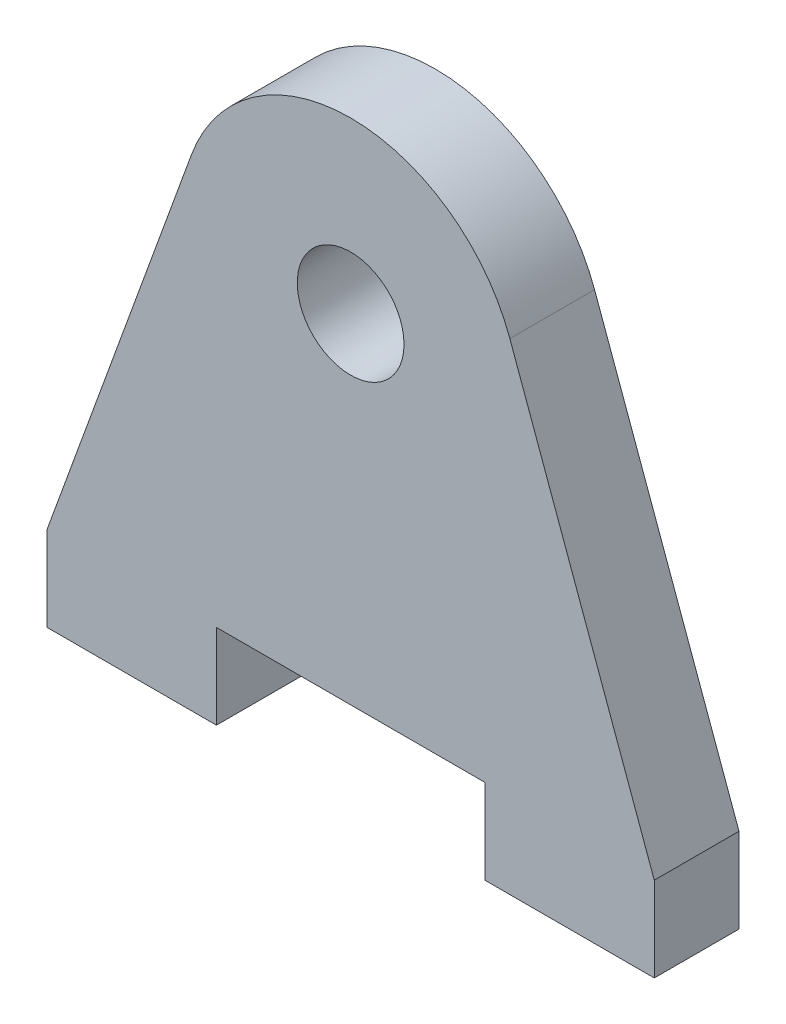
SolidWorks part; units mm, degrees
ref_plane "Front Plane" through (0, 0, 0) normal (0, 0, 1) x (1, 0, 0)
ref_plane "Top Plane" through (0, 0, 0) normal (0, 1, 0) x (1, 0, 0)
ref_plane "Right Plane" through (0, 0, 0) normal (1, 0, 0) x (0, 0, -1)
sketch "Sketch2" plane through (0, 0, 0) normal (0, 0, 1) x (1, 0, 0)
  line L0 (-11.9341, 4.3437) -> (-22.7599, -25.4)
  line L1 (-22.7599, -25.4) -> (22.7599, -25.4)
  line L2 (22.7599, -25.4) -> (11.9341, 4.3437)
  line L3 (-6.0308, -12.7) -> (4.8246, -12.7) construction
  line L4 (22.7599, -25.4) -> (22.7599, -4.7274) construction
  line L6 (-22.7599, -25.4) -> (-10.0599, -25.4)
  line L7 (-22.7599, -25.4) -> (-22.7599, -31.75)
  line L8 (-22.7599, -31.75) -> (-10.0599, -31.75)
  line L9 (-10.0599, -25.4) -> (-10.0599, -31.75)
  line L10 (22.7599, -25.4) -> (10.0599, -25.4)
  line L11 (22.7599, -25.4) -> (22.7599, -31.75)
  line L12 (22.7599, -31.75) -> (10.0599, -31.75)
  line L13 (10.0599, -25.4) -> (10.0599, -31.75)
  circle A0 centre (0, 0) radius 4
  arc A1 (11.9341, 4.3437) -> (-11.9341, 4.3437) centre (0, 0) ccw
  circle A2 centre (0, 0) radius 12.7 construction
  dimension "D1" = 8
  dimension "D2" = 25.4
  dimension "D3" = 12.7
  dimension "D4" = 20
  dimension "D5" = 6.35
  dimension "D6" = 12.7
extrude "Boss-Extrude1" add sketch "Sketch2" along normal blind 6.35 contours L9 L1 L7 L8 | L2 A1 L0 L1 A0 | L1 L13 L12 L11
